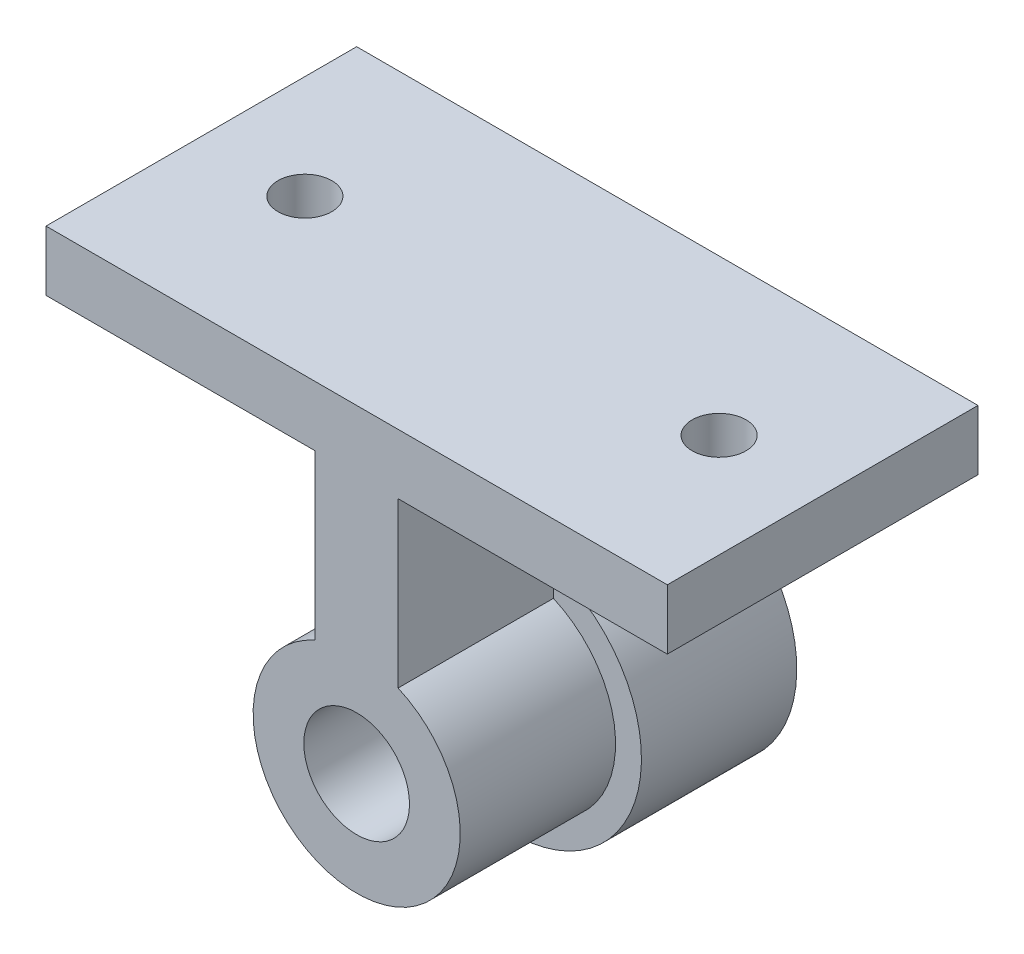
SolidWorks part; units mm, degrees
ref_plane "Front Plane" through (0, 0, 0) normal (0, 0, 1) x (1, 0, 0)
ref_plane "Top Plane" through (0, 0, 0) normal (0, 1, 0) x (1, 0, 0)
ref_plane "Right Plane" through (0, 0, 0) normal (1, 0, 0) x (0, 0, -1)
sketch "Sketch1" plane through (0, 0, 0) normal (0, 1, 0) x (1, 0, 0)
  line L1 (-30, 15) -> (30, 15)
  line L2 (-30, 15) -> (-30, -15)
  line L3 (-30, -15) -> (30, -15)
  line L4 (30, 15) -> (30, -15)
  line L5 (-30, 15) -> (30, -15) construction
  line L6 (-30, -15) -> (30, 15) construction
  point P0 (0, 0)
  dimension "D1" = 30
  dimension "D2" = 60
extrude "Boss-Extrude1" add sketch "Sketch1" along normal blind 5.8
sketch "Sketch2" plane through (0, 0, 0) normal (0, 1, 0) x (1, 0, 0)
  circle A0 centre (-20, 0) radius 2.6
  point P2 (-23.0421, 6.9818)
  dimension "D1" = 5.2
  dimension "D2" = 20
  dimension "D3" = 0
extrude "Cut-Extrude1" cut sketch "Sketch2" along normal blind 6
mirror "Mirror1" about plane through (0, 0, 0) normal (1, 0, 0) of "Cut-Extrude1"
sketch "Sketch3" plane through (0, 0, 0) normal (0, 0, 1) x (1, 0, 0)
  line L5 (30, 0) -> (-30, 0) construction
  line L8 (-4, 0) -> (4, 0)
  line L14 (-4, -15.8348) -> (-4, 0)
  line L15 (4, -15.8348) -> (4, 0)
  circle A0 centre (0, -25) radius 5.1
  arc A1 (-4, -15.8348) -> (4, -15.8348) centre (0, -25) ccw
  point P2 (-5.0353, -16.3602)
  point P3 (0, -11.6146)
  point P6 (0, 0)
  point P8 (2.0131, -13.8098)
  point P11 (-14.9873, -12.0741)
  point P12 (0, -11.6146)
  dimension "D1" = 20
  dimension "D2" = 10.2
  dimension "D3" = 25
  dimension "D4" = 0
  dimension "D5" = 8
  dimension "D6" = 0
  dimension "D7" = 4
extrude "Boss-Extrude2" add sketch "Sketch3" along normal blind 15
sketch "Sketch4" plane through (0, 0, 0) normal (0, 0, 1) x (1, 0, 0)
  line L0 (30, 0) -> (-30, 0) construction
  line L2 (-6, -14.0341) -> (-6, 0)
  line L3 (-6, 0) -> (6, 0)
  line L4 (6, -14.0341) -> (6, 0)
  circle A0 centre (0, -25) radius 5.1 construction
  circle A1 centre (0, -25) radius 5.1
  arc A2 (-6, -14.0341) -> (6, -14.0341) centre (0, -25) ccw
  point P4 (0, -7.2788)
  point P8 (5.3813, -13.7176)
  point P11 (0, 0)
  dimension "D1" = 25
  dimension "D2" = 12
  dimension "D3" = 6
  dimension "D4" = 0
extrude "Boss-Extrude3" add sketch "Sketch4" against normal blind 15
sketch "Sketch5" plane through (0, 0, -15) normal (0, 0, -1) x (-1, 0, 0)
  circle A0 centre (0, -25) radius 10.75
  dimension "D1" = 21.5
extrude "Cut-Extrude2" cut sketch "Sketch5" against normal blind 11 contours A0
